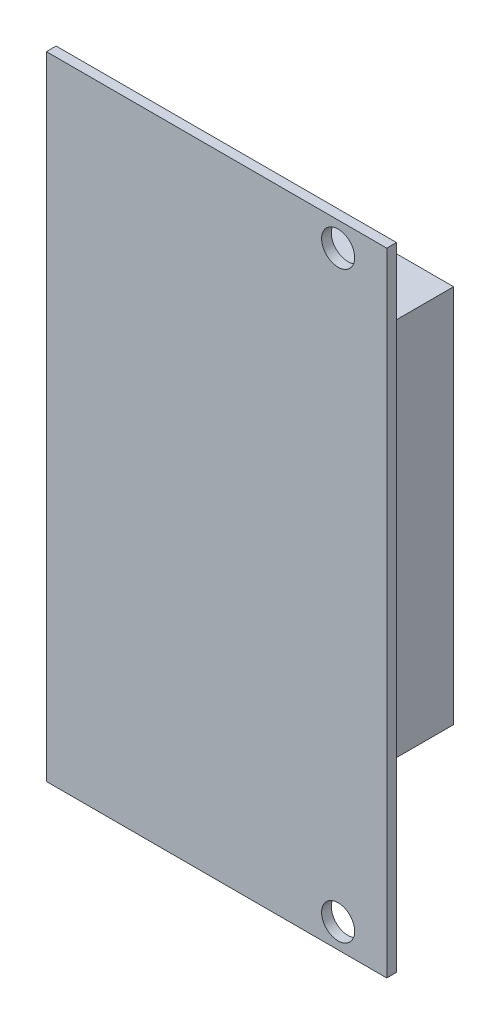
SolidWorks part; units mm, degrees
ref_plane "Front Plane" through (0, 0, 0) normal (0, 0, 1) x (1, 0, 0)
ref_plane "Top Plane" through (0, 0, 0) normal (0, 1, 0) x (1, 0, 0)
ref_plane "Right Plane" through (0, 0, 0) normal (1, 0, 0) x (0, 0, -1)
sketch "Sketch1" plane through (0, 0, 0) normal (0, 0, 1) x (1, 0, 0)
  line L1 (-17.5, -32.5) -> (17.5, -32.5)
  line L2 (-17.5, -32.5) -> (-17.5, 32.5)
  line L3 (-17.5, 32.5) -> (17.5, 32.5)
  line L4 (17.5, -32.5) -> (17.5, 32.5)
  line L5 (-17.5, -32.5) -> (17.5, 32.5) construction
  line L6 (-17.5, 32.5) -> (17.5, -32.5) construction
  point P0 (0, 0)
extrude "Boss-Extrude1" add sketch "Sketch1" against normal blind 1
ref_plane "Plane_1" through (0, 0, 0) normal (0, 0, 1) x (1, 0, 0)
sketch "Sketch2" plane through (0, 0, 0) normal (0, 0, 1) x (1, 0, 0)
  line L1 (-11.375, -19.5) -> (11.375, -19.5)
  line L2 (-11.375, -19.5) -> (-11.375, 19.5)
  line L3 (-11.375, 19.5) -> (11.375, 19.5)
  line L4 (11.375, -19.5) -> (11.375, 19.5)
  line L5 (-11.375, -19.5) -> (11.375, 19.5) construction
  line L6 (-11.375, 19.5) -> (11.375, -19.5) construction
  point P0 (0, 0)
extrude "Boss-Extrude2" add sketch "Sketch2" against normal blind 13
sketch "Sketch3" plane through (0, 0, 0) normal (0, 0, 1) x (1, 0, 0)
  circle A0 centre (0, -30) radius 1.7
  circle A1 centre (0, 30) radius 1.7
sketch "Sketch4" plane through (0, 0, 0) normal (0, 0, 1) x (1, 0, 0)
  circle A0 centre (12.5, -30) radius 1.7
  circle A1 centre (12.5, 30) radius 1.7
extrude "Hai_lo_M3_trung_tru_treo" cut sketch "Sketch4" along normal through all and the other way through all
